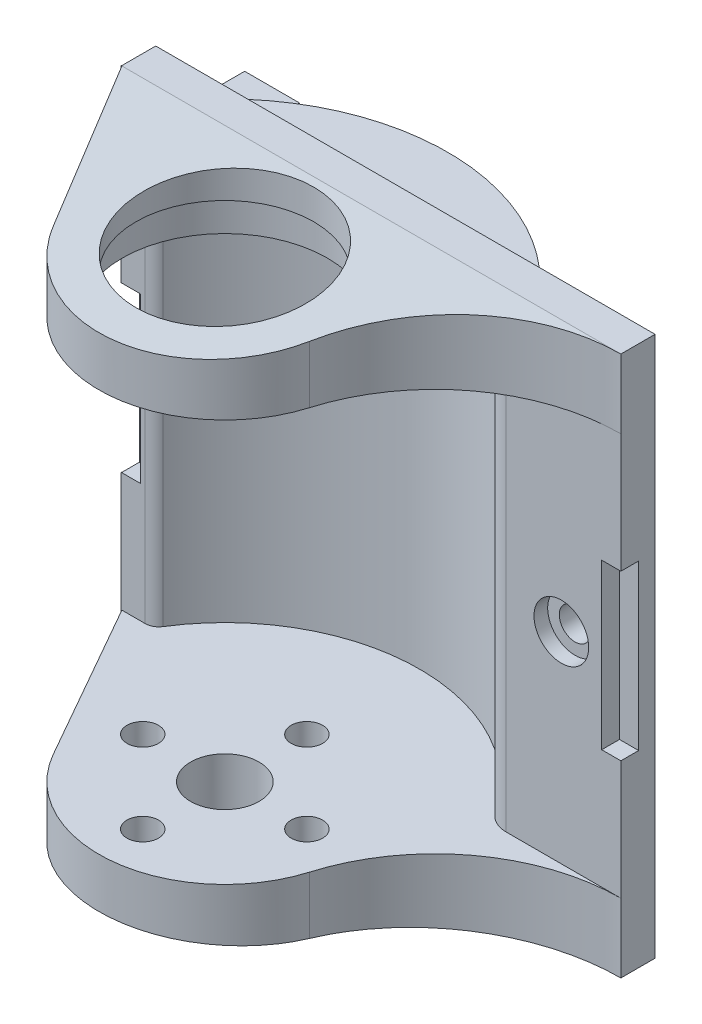
SolidWorks part; units mm, degrees
ref_plane "前视基准面" through (0, 0, 0) normal (0, 0, 1) x (1, 0, 0)
ref_plane "上视基准面" through (0, 0, 0) normal (0, 1, 0) x (1, 0, 0)
ref_plane "右视基准面" through (0, 0, 0) normal (1, 0, 0) x (0, 0, -1)
sketch "草图1" plane through (0, 0, 0) normal (0, 1, 0) x (1, 0, 0)
  circle A1 centre (0, 0) radius 16.3
  dimension "D1" = 32.6
extrude "凸台-拉伸1" add sketch "草图1" along normal mid plane 39.5
sketch "草图2" plane through (0, -19.75, 0) normal (0, -1, 0) x (1, 0, 0)
  line L1 (-14.65, -7.1) -> (21.85, -7.1)
  line L2 (-14.65, -7.1) -> (-14.65, -9.6)
  line L3 (-14.65, -9.6) -> (21.85, -9.6)
  line L4 (21.85, -7.1) -> (21.85, -9.6)
  dimension "D1" = 2.5
  dimension "D2" = 9.6
  dimension "D3" = 36.5
  dimension "D4" = 14.65
extrude "凸台-拉伸2" add sketch "草图2" against normal through all
sketch "草图3" plane through (0, -19.75, 0) normal (0, -1, 0) x (1, 0, 0)
  line L1 (21.85, -7.1) -> (-22.9944, -7.1)
  line L2 (21.85, -7.1) -> (21.85, 18.4067)
  line L3 (21.85, 18.4067) -> (-22.9944, 18.4067)
  line L4 (-22.9944, -7.1) -> (-22.9944, 18.4067)
extrude "切除-拉伸1" cut sketch "草图3" against normal blind 50
sketch "草图4" plane through (0, -19.75, 0) normal (0, -1, 0) x (1, 0, 0)
  line L0 (-14.65, -7.1462) -> (-7.9965, 4.5492)
  line L1 (21.85, -7.1) -> (21.85, 7.9567) construction
  line L2 (-14.65, -7.1462) -> (21.85, -7.1)
  arc A0 (8.8187, 2.6213) -> (-7.9965, 4.5492) centre (0, 0) ccw
  arc A1 (8.8187, 2.6213) -> (21.85, -7.1) centre (21.85, 6.4949) ccw
  dimension "D1" = 18.4
extrude "凸台-拉伸3" add sketch "草图4" against normal blind 5.05
mirror "镜向1" about plane through (0, 0, 0) normal (0, 1, 0) of "凸台-拉伸3"
sketch "草图5" plane through (0, -14.7, 0) normal (0, 1, 0) x (1, 0, 0)
  circle A0 centre (0, 0) radius 14.25
  dimension "D1" = 28.5
extrude "切除-拉伸2" cut sketch "草图5" along normal up to surface (29.4 mm away) up to face at (1.768, 14.7, -0.9093)
sketch "草图6" plane through (0, -14.7, 0) normal (0, 1, 0) x (1, 0, 0)
  circle A0 centre (0, 0) radius 2.5
  dimension "D1" = 5
extrude "切除-拉伸3" cut sketch "草图6" against normal through all
sketch "草图9" plane through (0, 19.75, 0) normal (0, 1, 0) x (1, 0, 0)
  circle A0 centre (0, 0) radius 7.5
  dimension "D1" = 15
extrude "切除-拉伸6" cut sketch "草图9" against normal up to next
sketch "草图12" plane through (0, 0, -7.1) normal (0, 0, 1) x (1, 0, 0)
  line L0 (0, 0) -> (30.0134, 0) construction
  line L1 (21.85, 14.7) -> (21.85, -14.7) construction
  circle A0 centre (17.5, 0) radius 1.15
  dimension "D1" = 2.3
  dimension "D2" = 4.35
extrude "切除-拉伸9" cut sketch "草图12" against normal through all
sketch "草图13" plane through (0, 0, -7.1) normal (0, 0, 1) x (1, 0, 0)
  circle A0 centre (17.5, 0) radius 2
  dimension "D1" = 4
extrude "切除-拉伸10" cut sketch "草图13" against normal blind 1
sketch "草图14" plane through (0, 0, -7.1) normal (0, 0, 1) x (1, 0, 0)
  line L0 (21.85, 14.7) -> (21.85, -14.7) construction
  line L1 (20.45, -6) -> (23.25, -6)
  line L2 (20.45, -6) -> (20.45, 6)
  line L3 (20.45, 6) -> (23.25, 6)
  line L4 (23.25, -6) -> (23.25, 6)
  line L5 (20.45, -6) -> (23.25, 6) construction
  line L6 (20.45, 6) -> (23.25, -6) construction
  point P0 (21.85, 0)
  dimension "12" = 12
  dimension "D2" = 2.8
extrude "切除-拉伸11" cut sketch "草图14" against normal blind 1.3
sketch "草图15" plane through (0, 0, -7.1) normal (0, 0, 1) x (1, 0, 0)
  line L0 (0, 0) -> (-23.1213, 0) construction
  line L1 (-14.6724, -19.75) -> (-14.6724, 19.75) construction
  line L2 (-16.0724, -6) -> (-13.2724, -6)
  line L3 (-16.0724, -6) -> (-16.0724, 6)
  line L4 (-16.0724, 6) -> (-13.2724, 6)
  line L5 (-13.2724, -6) -> (-13.2724, 6)
  line L6 (-16.0724, -6) -> (-13.2724, 6) construction
  line L7 (-16.0724, 6) -> (-13.2724, -6) construction
  point P3 (-14.6724, 0)
  dimension "D1" = 12
  dimension "D2" = 2.8
extrude "切除-拉伸12" cut sketch "草图15" against normal blind 1.3
ref_plane "基准面1" through (0, 0, -15.1) normal (0, 0, -1) x (-1, 0, 0)
sketch "草图16" plane through (0, 0, -15.1) normal (0, 0, -1) x (-1, 0, 0)
  line L0 (14.65, 19.75) -> (14.65, -19.75) construction
  line L1 (9.65, 10.9) -> (13.65, 10.9)
  line L2 (9.65, 10.9) -> (9.65, 15.9)
  line L3 (9.65, 15.9) -> (13.65, 15.9)
  line L4 (13.65, 10.9) -> (13.65, 15.9)
  line L5 (9.65, 10.9) -> (13.65, 15.9) construction
  line L6 (9.65, 15.9) -> (13.65, 10.9) construction
  line L7 (0, 0) -> (27.535, 0) construction
  point P0 (11.65, 13.4)
  dimension "D1" = 1
  dimension "D2" = 10.9
  dimension "D3" = 5
  dimension "D4" = 4
extrude "凸台-拉伸5" add sketch "草图16" against normal up to surface (1.9635 mm away)
mirror "镜向4" about plane through (0, 0, 0) normal (0, 1, 0) of "凸台-拉伸5"
sketch "草图17" plane through (0, 0, -15.1) normal (0, 0, -1) x (-1, 0, 0)
  line L0 (11.65, 15.9) -> (11.65, 12.48) construction
  line L1 (13.65, 15.9) -> (9.65, 15.9) construction
  line L2 (13.65, 13.4) -> (11.1035, 13.4) construction
  line L3 (13.65, 10.9) -> (13.65, 15.9) construction
  line L5 (11.15, 12.4) -> (12.15, 12.4)
  line L6 (11.15, 12.4) -> (11.15, 14.4)
  line L7 (11.15, 14.4) -> (12.15, 14.4)
  line L8 (12.15, 12.4) -> (12.15, 14.4)
  line L9 (11.15, 12.4) -> (12.15, 14.4) construction
  line L10 (11.15, 14.4) -> (12.15, 12.4) construction
  point P8 (11.65, 13.4)
  dimension "D1" = 2
  dimension "D2" = 1
extrude "切除-拉伸13" cut sketch "草图17" against normal blind 2.5
mirror "镜向5" about plane through (0, 0, 0) normal (0, 1, 0) of "切除-拉伸13"
sketch "草图19" plane through (0, 19.75, 0) normal (0, 1, 0) x (1, 0, 0)
  circle A1 centre (0, 0) radius 6.5
  circle A2 centre (0, 0) radius 8.519
  dimension "D1" = 13
extrude "凸台-拉伸6" add sketch "草图19" against normal blind 2.25
sketch "草图20" plane through (0, -19.75, 0) normal (0, -1, 0) x (1, 0, 0)
  circle A0 centre (0, 6) radius 1.15
  dimension "D1" = 2.3
  dimension "D2" = 6
extrude "切除-拉伸18" cut sketch "草图20" against normal up to next
pattern_circular "阵列(圆周)1" count 4 over 360 about axis through (0, 0, 0) along (0, 1, 0) of "切除-拉伸18"
sketch "草图7" plane through (-14.65, 0, 0) normal (-1, 0, 0) x (0, 0, 1)
  line L0 (-7.1, 19.75) -> (9.2, 18.3239)
  line L1 (9.2, 14.7) -> (9.2, 19.75) construction
  line L2 (9.2, 18.3239) -> (9.2, 19.75)
  line L3 (9.2, 19.75) -> (-7.1, 19.75)
  dimension "D1" = 5
extrude "切除-拉伸8" cut sketch "草图7" against normal through all
mirror "镜向3" about plane through (0, 0, 0) normal (0, 1, 0) of "切除-拉伸8"
sketch "草图18" plane through (0, 0, -9.6) normal (0, 0, -1) x (-1, 0, 0)
  line L0 (-13.1731, 19.75) -> (-13.1731, -19.75) construction
  line L1 (13.1731, 19.75) -> (-13.1731, 19.75)
  line L2 (13.1731, 19.75) -> (13.1731, 17)
  line L3 (13.1731, 17) -> (-13.1731, 17)
  line L4 (-13.1731, 19.75) -> (-13.1731, 17)
  dimension "D1" = 2.75
extrude "切除-拉伸16" cut sketch "草图18" along normal blind 12.5
mirror "镜向6" about plane through (0, 0, 0) normal (0, 1, 0) of "切除-拉伸16"
fillet "圆角1" radius 2 1 edges at (12.3553, 0, -7.1)
fillet "圆角2" radius 1 1 edges at (-12.3553, 0, -7.1)
